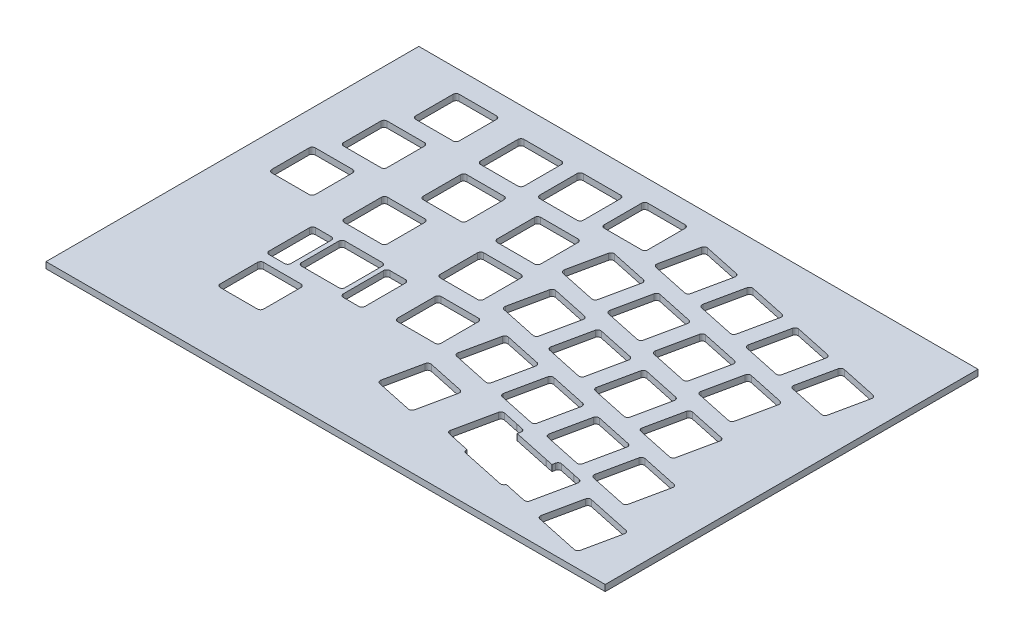
SolidWorks part; units mm, degrees
ref_plane "Front Plane" through (0, 0, 0) normal (0, 0, 1) x (1, 0, 0)
ref_plane "Top Plane" through (0, 0, 0) normal (0, 1, 0) x (1, 0, 0)
ref_plane "Right Plane" through (0, 0, 0) normal (1, 0, 0) x (0, 0, -1)
sketch "Sketch1" plane through (0, 0, 0) normal (0, 1, 0) x (1, 0, 0)
  line L1 (3, -3) -> (-177, -3) construction
  line L2 (3, -3) -> (3, 117) construction
  line L3 (3, 117) -> (-177, 117) construction
  line L4 (-177, -3) -> (-177, 117) construction
  line L5 (3, -3) -> (-177, 117) construction
  line L6 (3, 117) -> (-177, -3) construction
  line L15 (3, -3) -> (-177, -3)
  line L16 (3, -3) -> (3, 117)
  line L17 (3, 117) -> (-177, 117)
  line L18 (-177, -3) -> (-177, 117)
  line L19 (3, -3) -> (-177, 117) construction
  line L20 (3, 117) -> (-177, -3) construction
  point P5 (-87, 57)
  point P6 (-87, 57)
  line B0 (-26.8584, 37.7422) -> (-29.3534, 26.0044)
  line B1 (-28.5831, 24.8183) -> (-16.8454, 22.3234)
  line B2 (-13.1644, 34.8314) -> (-15.6593, 23.0936)
  line B3 (-25.6724, 38.5124) -> (-13.9346, 36.0175)
  line B4 (-32.2084, 58.3522) -> (-34.7034, 46.6144)
  line B5 (-33.9331, 45.4283) -> (-22.1954, 42.9334)
  line B6 (-18.5144, 55.4414) -> (-21.0093, 43.7036)
  line B7 (-31.0224, 59.1224) -> (-19.2846, 56.6275)
  line B8 (-32.9084, 77.9822) -> (-35.4034, 66.2444)
  line B9 (-34.6331, 65.0583) -> (-22.8954, 62.5634)
  line B10 (-19.2144, 75.0714) -> (-21.7093, 63.3336)
  line B11 (-31.7224, 78.7524) -> (-19.9846, 76.2575)
  line B12 (-19.6284, 94.6322) -> (-22.1234, 82.8944)
  line B13 (-21.3531, 81.7083) -> (-9.6154, 79.2134)
  line B14 (-5.9344, 91.7214) -> (-8.4293, 79.9836)
  line B15 (-18.4424, 95.4024) -> (-6.7046, 92.9075)
  line B16 (-45.4921, 41.7029) -> (-47.9871, 29.9651)
  line B17 (-47.2168, 28.7791) -> (-35.4791, 26.2841)
  line B18 (-31.7981, 38.7921) -> (-34.293, 27.0543)
  line B19 (-44.3061, 42.4731) -> (-32.5683, 39.9782)
  line B20 (-50.8421, 62.3129) -> (-53.3371, 50.5751)
  line B21 (-52.5668, 49.3891) -> (-40.8291, 46.8941)
  line B22 (-37.1481, 59.4021) -> (-39.643, 47.6643)
  line B23 (-49.6561, 63.0831) -> (-37.9183, 60.5882)
  line B24 (-51.5421, 81.9429) -> (-54.0371, 70.2051)
  line B25 (-53.2668, 69.0191) -> (-41.5291, 66.5241)
  line B26 (-37.8481, 79.0321) -> (-40.343, 67.2943)
  line B27 (-50.3561, 82.7131) -> (-38.6183, 80.2182)
  line B28 (-38.2621, 98.5929) -> (-40.7571, 86.8551)
  line B29 (-39.9868, 85.6691) -> (-28.2491, 83.1741)
  line B30 (-24.5681, 95.6821) -> (-27.063, 83.9443)
  line B31 (-37.0761, 99.3631) -> (-25.3383, 96.8682)
  line B32 (-64.1259, 45.6636) -> (-66.6208, 33.9258)
  line B33 (-65.8506, 32.7398) -> (-54.1128, 30.2448)
  line B34 (-50.4318, 42.7528) -> (-52.9267, 31.0151)
  line B35 (-62.9398, 46.4338) -> (-51.202, 43.9389)
  line B36 (-69.4759, 66.2736) -> (-71.9708, 54.5358)
  line B37 (-71.2006, 53.3498) -> (-59.4628, 50.8548)
  line B38 (-55.7818, 63.3628) -> (-58.2767, 51.6251)
  line B39 (-68.2898, 67.0438) -> (-56.552, 64.5489)
  line B40 (-70.1759, 85.9036) -> (-72.6708, 74.1658)
  line B41 (-71.9006, 72.9798) -> (-60.1628, 70.4848)
  line B42 (-56.4818, 82.9928) -> (-58.9767, 71.2551)
  line B43 (-68.9898, 86.6738) -> (-57.252, 84.1789)
  line B44 (-56.8959, 102.5536) -> (-59.3908, 90.8158)
  line B45 (-58.6206, 89.6298) -> (-46.8828, 87.1348)
  line B46 (-43.2018, 99.6428) -> (-45.6967, 87.9051)
  line B47 (-55.7098, 103.3238) -> (-43.972, 100.8289)
  line B48 (-88.1096, 70.2343) -> (-90.6045, 58.4965)
  line B49 (-89.8343, 57.3105) -> (-78.0965, 54.8155)
  line B50 (-74.4155, 67.3236) -> (-76.9104, 55.5858)
  line B51 (-86.9235, 71.0046) -> (-75.1857, 68.5096)
  line B52 (-82.7596, 49.6243) -> (-85.2545, 37.8865)
  line B53 (-84.4843, 36.7005) -> (-72.7465, 34.2055)
  line B54 (-69.0655, 46.7136) -> (-71.5604, 34.9758)
  line B55 (-81.5735, 50.3946) -> (-69.8357, 47.8996)
  line B56 (-87.5696, 29.6343) -> (-90.0645, 17.8965)
  line B57 (-89.2943, 16.7105) -> (-77.5565, 14.2155)
  line B58 (-73.8755, 26.7236) -> (-76.3704, 14.9858)
  line B59 (-86.3835, 30.4046) -> (-74.6457, 27.9096)
  line B60 (-88.8096, 89.8643) -> (-91.3045, 78.1265)
  line B61 (-90.5343, 76.9405) -> (-78.7965, 74.4455)
  line B62 (-75.1155, 86.9536) -> (-77.6104, 75.2158)
  line B63 (-87.6235, 90.6346) -> (-75.8857, 88.1396)
  line B64 (-75.5296, 106.5143) -> (-78.0245, 94.7765)
  line B65 (-77.2543, 93.5905) -> (-65.5165, 91.0955)
  line B66 (-61.8355, 103.6036) -> (-64.3304, 91.8658)
  line B67 (-74.3435, 107.2846) -> (-62.6057, 104.7896)
  line B68 (-110.01, 68.91) -> (-110.01, 56.91)
  line B69 (-109.01, 55.91) -> (-97.01, 55.91)
  line B70 (-96.01, 68.91) -> (-96.01, 56.91)
  line B71 (-109.01, 69.91) -> (-97.01, 69.91)
  line B72 (-134.52, 87.96) -> (-134.52, 75.96)
  line B73 (-133.52, 74.96) -> (-121.52, 74.96)
  line B74 (-120.52, 87.96) -> (-120.52, 75.96)
  line B75 (-133.52, 88.96) -> (-121.52, 88.96)
  line B76 (-140.97, 68.91) -> (-140.97, 56.91)
  line B77 (-139.97, 55.91) -> (-127.97, 55.91)
  line B78 (-126.97, 68.91) -> (-126.97, 56.91)
  line B79 (-139.97, 69.91) -> (-127.97, 69.91)
  line B80 (-110.71, 87.96) -> (-110.71, 75.96)
  line B81 (-109.71, 74.96) -> (-97.71, 74.96)
  line B82 (-96.71, 87.96) -> (-96.71, 75.96)
  line B83 (-109.71, 88.96) -> (-97.71, 88.96)
  line B84 (-97.43, 109.15) -> (-97.43, 97.15)
  line B85 (-96.43, 96.15) -> (-84.43, 96.15)
  line B86 (-83.43, 109.15) -> (-83.43, 97.15)
  line B87 (-96.43, 110.15) -> (-84.43, 110.15)
  line B88 (-116.07, 107.01) -> (-116.07, 95.01)
  line B89 (-115.07, 94.01) -> (-103.07, 94.01)
  line B90 (-102.07, 107.01) -> (-102.07, 95.01)
  line B91 (-115.07, 108.01) -> (-103.07, 108.01)
  line B92 (-135.12, 107.01) -> (-135.12, 95.01)
  line B93 (-134.12, 94.01) -> (-122.12, 94.01)
  line B94 (-121.12, 107.01) -> (-121.12, 95.01)
  line B95 (-134.12, 108.01) -> (-122.12, 108.01)
  line B96 (-104.66, 49.86) -> (-104.66, 37.86)
  line B97 (-103.66, 36.86) -> (-91.66, 36.86)
  line B98 (-90.66, 49.86) -> (-90.66, 37.86)
  line B99 (-103.66, 50.86) -> (-91.66, 50.86)
  line B100 (-142.75, 30.81) -> (-142.75, 18.81)
  line B101 (-141.75, 17.81) -> (-129.75, 17.81)
  line B102 (-128.75, 30.81) -> (-128.75, 18.81)
  line B103 (-141.75, 31.81) -> (-129.75, 31.81)
  line B104 (-158.14, 109.15) -> (-158.14, 97.15)
  line B105 (-157.14, 96.15) -> (-145.14, 96.15)
  line B106 (-144.14, 109.15) -> (-144.14, 97.15)
  line B107 (-157.14, 110.15) -> (-145.14, 110.15)
  line B108 (-162.3, 90.1) -> (-162.3, 78.1)
  line B109 (-161.3, 77.1) -> (-149.3, 77.1)
  line B110 (-148.3, 90.1) -> (-148.3, 78.1)
  line B111 (-161.3, 91.1) -> (-149.3, 91.1)
  line B112 (-135.61, 49.86) -> (-135.61, 37.86)
  line B113 (-134.61, 36.86) -> (-122.61, 36.86)
  line B114 (-121.61, 49.86) -> (-121.61, 37.86)
  line B115 (-134.61, 50.86) -> (-122.61, 50.86)
  line B116 (-166.37, 71.05) -> (-166.37, 59.05)
  line B117 (-165.37, 58.05) -> (-153.37, 58.05)
  line B118 (-152.37, 71.05) -> (-152.37, 59.05)
  line B119 (-165.37, 72.05) -> (-153.37, 72.05)
  line B120 (-113.172, 35.86) -> (-113.172, 48.86)
  line B121 (-114.172, 49.86) -> (-119.172, 49.86)
  line B122 (-120.172, 48.86) -> (-120.172, 35.86)
  line B123 (-119.172, 34.86) -> (-114.172, 34.86)
  line B124 (-137.048, 35.86) -> (-137.048, 48.86)
  line B125 (-138.048, 49.86) -> (-143.048, 49.86)
  line B126 (-144.048, 48.86) -> (-144.048, 35.86)
  line B127 (-143.048, 34.86) -> (-138.048, 34.86)
  line B128 (-53.7643, 10.6905) -> (-42.0265, 8.1955)
  line B129 (-40.8379, 8.9776) -> (-40.8404, 8.9658)
  line B130 (-38.5707, 8.4906) -> (-40.7417, 8.9521)
  line B131 (-38.4557, 8.4589) -> (-33.565, 7.4193)
  line B132 (-32.3789, 8.1896) -> (-29.6761, 20.9055)
  line B133 (-30.4463, 22.0915) -> (-32.6174, 22.553)
  line B134 (-32.7323, 22.5847) -> (-37.6231, 23.6243)
  line B135 (-38.8091, 22.8541) -> (-39.0195, 21.8641)
  line B136 (-41.3143, 22.3569) -> (-39.1157, 21.8896)
  line B137 (-41.4072, 22.3814) -> (-53.1449, 24.8763)
  line B138 (-53.2382, 24.8916) -> (-53.0303, 25.8696)
  line B139 (-53.8006, 27.0556) -> (-55.9716, 27.5171)
  line B140 (-56.0866, 27.5488) -> (-60.9773, 28.5884)
  line B141 (-62.1634, 27.8182) -> (-64.8662, 15.1022)
  line B142 (-61.9249, 13.4547) -> (-64.096, 13.9162)
  line B143 (-61.81, 13.423) -> (-56.9192, 12.3834)
  line B144 (-56.0557, 11.1823) -> (-53.8571, 10.7149)
  line B145 (-24.0476, 17.6691) -> (-26.5425, 5.9314)
  line B146 (-25.7723, 4.7453) -> (-11.7065, 1.7555)
  line B147 (-8.0255, 14.2636) -> (-10.5204, 2.5258)
  line B148 (-22.8615, 18.4394) -> (-8.7957, 15.4496)
  arc B149 (-29.3534, 26.0044) -> (-28.5831, 24.8183) centre (-28.3752, 25.7965) ccw
  arc B150 (-16.8454, 22.3234) -> (-15.6593, 23.0936) centre (-16.6374, 23.3015) ccw
  arc B151 (-13.1644, 34.8314) -> (-13.9346, 36.0175) centre (-14.1425, 35.0393) ccw
  arc B152 (-25.6724, 38.5124) -> (-26.8584, 37.7422) centre (-25.8803, 37.5343) ccw
  arc B153 (-34.7034, 46.6144) -> (-33.9331, 45.4283) centre (-33.7252, 46.4065) ccw
  arc B154 (-22.1954, 42.9334) -> (-21.0093, 43.7036) centre (-21.9874, 43.9115) ccw
  arc B155 (-18.5144, 55.4414) -> (-19.2846, 56.6275) centre (-19.4925, 55.6493) ccw
  arc B156 (-31.0224, 59.1224) -> (-32.2084, 58.3522) centre (-31.2303, 58.1443) ccw
  arc B157 (-35.4034, 66.2444) -> (-34.6331, 65.0583) centre (-34.4252, 66.0365) ccw
  arc B158 (-22.8954, 62.5634) -> (-21.7093, 63.3336) centre (-22.6874, 63.5415) ccw
  arc B159 (-19.2144, 75.0714) -> (-19.9846, 76.2575) centre (-20.1925, 75.2793) ccw
  arc B160 (-31.7224, 78.7524) -> (-32.9084, 77.9822) centre (-31.9303, 77.7743) ccw
  arc B161 (-22.1234, 82.8944) -> (-21.3531, 81.7083) centre (-21.1452, 82.6865) ccw
  arc B162 (-9.6154, 79.2134) -> (-8.4293, 79.9836) centre (-9.4074, 80.1915) ccw
  arc B163 (-5.9344, 91.7214) -> (-6.7046, 92.9075) centre (-6.9125, 91.9293) ccw
  arc B164 (-18.4424, 95.4024) -> (-19.6284, 94.6322) centre (-18.6503, 94.4243) ccw
  arc B165 (-47.9871, 29.9651) -> (-47.2168, 28.7791) centre (-47.0089, 29.7572) ccw
  arc B166 (-35.4791, 26.2841) -> (-34.293, 27.0543) centre (-35.2712, 27.2623) ccw
  arc B167 (-31.7981, 38.7921) -> (-32.5683, 39.9782) centre (-32.7762, 39) ccw
  arc B168 (-44.3061, 42.4731) -> (-45.4921, 41.7029) centre (-44.514, 41.495) ccw
  arc B169 (-53.3371, 50.5751) -> (-52.5668, 49.3891) centre (-52.3589, 50.3672) ccw
  arc B170 (-40.8291, 46.8941) -> (-39.643, 47.6643) centre (-40.6212, 47.8723) ccw
  arc B171 (-37.1481, 59.4021) -> (-37.9183, 60.5882) centre (-38.1262, 59.61) ccw
  arc B172 (-49.6561, 63.0831) -> (-50.8421, 62.3129) centre (-49.864, 62.105) ccw
  arc B173 (-54.0371, 70.2051) -> (-53.2668, 69.0191) centre (-53.0589, 69.9972) ccw
  arc B174 (-41.5291, 66.5241) -> (-40.343, 67.2943) centre (-41.3212, 67.5023) ccw
  arc B175 (-37.8481, 79.0321) -> (-38.6183, 80.2182) centre (-38.8262, 79.24) ccw
  arc B176 (-50.3561, 82.7131) -> (-51.5421, 81.9429) centre (-50.564, 81.735) ccw
  arc B177 (-40.7571, 86.8551) -> (-39.9868, 85.6691) centre (-39.7789, 86.6472) ccw
  arc B178 (-28.2491, 83.1741) -> (-27.063, 83.9443) centre (-28.0412, 84.1523) ccw
  arc B179 (-24.5681, 95.6821) -> (-25.3383, 96.8682) centre (-25.5462, 95.89) ccw
  arc B180 (-37.0761, 99.3631) -> (-38.2621, 98.5929) centre (-37.284, 98.385) ccw
  arc B181 (-66.6208, 33.9258) -> (-65.8506, 32.7398) centre (-65.6426, 33.7179) ccw
  arc B182 (-54.1128, 30.2448) -> (-52.9267, 31.0151) centre (-53.9049, 31.223) ccw
  arc B183 (-50.4318, 42.7528) -> (-51.202, 43.9389) centre (-51.4099, 42.9607) ccw
  arc B184 (-62.9398, 46.4338) -> (-64.1259, 45.6636) centre (-63.1477, 45.4557) ccw
  arc B185 (-71.9708, 54.5358) -> (-71.2006, 53.3498) centre (-70.9926, 54.3279) ccw
  arc B186 (-59.4628, 50.8548) -> (-58.2767, 51.6251) centre (-59.2549, 51.833) ccw
  arc B187 (-55.7818, 63.3628) -> (-56.552, 64.5489) centre (-56.7599, 63.5707) ccw
  arc B188 (-68.2898, 67.0438) -> (-69.4759, 66.2736) centre (-68.4977, 66.0657) ccw
  arc B189 (-72.6708, 74.1658) -> (-71.9006, 72.9798) centre (-71.6926, 73.9579) ccw
  arc B190 (-60.1628, 70.4848) -> (-58.9767, 71.2551) centre (-59.9549, 71.463) ccw
  arc B191 (-56.4818, 82.9928) -> (-57.252, 84.1789) centre (-57.4599, 83.2007) ccw
  arc B192 (-68.9898, 86.6738) -> (-70.1759, 85.9036) centre (-69.1977, 85.6957) ccw
  arc B193 (-59.3908, 90.8158) -> (-58.6206, 89.6298) centre (-58.4126, 90.6079) ccw
  arc B194 (-46.8828, 87.1348) -> (-45.6967, 87.9051) centre (-46.6749, 88.113) ccw
  arc B195 (-43.2018, 99.6428) -> (-43.972, 100.8289) centre (-44.1799, 99.8507) ccw
  arc B196 (-55.7098, 103.3238) -> (-56.8959, 102.5536) centre (-55.9177, 102.3457) ccw
  arc B197 (-90.6045, 58.4965) -> (-89.8343, 57.3105) centre (-89.6264, 58.2886) ccw
  arc B198 (-78.0965, 54.8155) -> (-76.9104, 55.5858) centre (-77.8886, 55.7937) ccw
  arc B199 (-74.4155, 67.3236) -> (-75.1857, 68.5096) centre (-75.3936, 67.5315) ccw
  arc B200 (-86.9235, 71.0046) -> (-88.1096, 70.2343) centre (-87.1314, 70.0264) ccw
  arc B201 (-85.2545, 37.8865) -> (-84.4843, 36.7005) centre (-84.2764, 37.6786) ccw
  arc B202 (-72.7465, 34.2055) -> (-71.5604, 34.9758) centre (-72.5386, 35.1837) ccw
  arc B203 (-69.0655, 46.7136) -> (-69.8357, 47.8996) centre (-70.0436, 46.9215) ccw
  arc B204 (-81.5735, 50.3946) -> (-82.7596, 49.6243) centre (-81.7814, 49.4164) ccw
  arc B205 (-90.0645, 17.8965) -> (-89.2943, 16.7105) centre (-89.0864, 17.6886) ccw
  arc B206 (-77.5565, 14.2155) -> (-76.3704, 14.9858) centre (-77.3486, 15.1937) ccw
  arc B207 (-73.8755, 26.7236) -> (-74.6457, 27.9096) centre (-74.8536, 26.9315) ccw
  arc B208 (-86.3835, 30.4046) -> (-87.5696, 29.6343) centre (-86.5914, 29.4264) ccw
  arc B209 (-91.3045, 78.1265) -> (-90.5343, 76.9405) centre (-90.3264, 77.9186) ccw
  arc B210 (-78.7965, 74.4455) -> (-77.6104, 75.2158) centre (-78.5886, 75.4237) ccw
  arc B211 (-75.1155, 86.9536) -> (-75.8857, 88.1396) centre (-76.0936, 87.1615) ccw
  arc B212 (-87.6235, 90.6346) -> (-88.8096, 89.8643) centre (-87.8314, 89.6564) ccw
  arc B213 (-78.0245, 94.7765) -> (-77.2543, 93.5905) centre (-77.0464, 94.5686) ccw
  arc B214 (-65.5165, 91.0955) -> (-64.3304, 91.8658) centre (-65.3086, 92.0737) ccw
  arc B215 (-61.8355, 103.6036) -> (-62.6057, 104.7896) centre (-62.8136, 103.8115) ccw
  arc B216 (-74.3435, 107.2846) -> (-75.5296, 106.5143) centre (-74.5514, 106.3064) ccw
  arc B217 (-110.01, 56.91) -> (-109.01, 55.91) centre (-109.01, 56.91) ccw
  arc B218 (-97.01, 55.91) -> (-96.01, 56.91) centre (-97.01, 56.91) ccw
  arc B219 (-96.01, 68.91) -> (-97.01, 69.91) centre (-97.01, 68.91) ccw
  arc B220 (-109.01, 69.91) -> (-110.01, 68.91) centre (-109.01, 68.91) ccw
  arc B221 (-134.52, 75.96) -> (-133.52, 74.96) centre (-133.52, 75.96) ccw
  arc B222 (-121.52, 74.96) -> (-120.52, 75.96) centre (-121.52, 75.96) ccw
  arc B223 (-120.52, 87.96) -> (-121.52, 88.96) centre (-121.52, 87.96) ccw
  arc B224 (-133.52, 88.96) -> (-134.52, 87.96) centre (-133.52, 87.96) ccw
  arc B225 (-140.97, 56.91) -> (-139.97, 55.91) centre (-139.97, 56.91) ccw
  arc B226 (-127.97, 55.91) -> (-126.97, 56.91) centre (-127.97, 56.91) ccw
  arc B227 (-126.97, 68.91) -> (-127.97, 69.91) centre (-127.97, 68.91) ccw
  arc B228 (-139.97, 69.91) -> (-140.97, 68.91) centre (-139.97, 68.91) ccw
  arc B229 (-110.71, 75.96) -> (-109.71, 74.96) centre (-109.71, 75.96) ccw
  arc B230 (-97.71, 74.96) -> (-96.71, 75.96) centre (-97.71, 75.96) ccw
  arc B231 (-96.71, 87.96) -> (-97.71, 88.96) centre (-97.71, 87.96) ccw
  arc B232 (-109.71, 88.96) -> (-110.71, 87.96) centre (-109.71, 87.96) ccw
  arc B233 (-97.43, 97.15) -> (-96.43, 96.15) centre (-96.43, 97.15) ccw
  arc B234 (-84.43, 96.15) -> (-83.43, 97.15) centre (-84.43, 97.15) ccw
  arc B235 (-83.43, 109.15) -> (-84.43, 110.15) centre (-84.43, 109.15) ccw
  arc B236 (-96.43, 110.15) -> (-97.43, 109.15) centre (-96.43, 109.15) ccw
  arc B237 (-116.07, 95.01) -> (-115.07, 94.01) centre (-115.07, 95.01) ccw
  arc B238 (-103.07, 94.01) -> (-102.07, 95.01) centre (-103.07, 95.01) ccw
  arc B239 (-102.07, 107.01) -> (-103.07, 108.01) centre (-103.07, 107.01) ccw
  arc B240 (-115.07, 108.01) -> (-116.07, 107.01) centre (-115.07, 107.01) ccw
  arc B241 (-135.12, 95.01) -> (-134.12, 94.01) centre (-134.12, 95.01) ccw
  arc B242 (-122.12, 94.01) -> (-121.12, 95.01) centre (-122.12, 95.01) ccw
  arc B243 (-121.12, 107.01) -> (-122.12, 108.01) centre (-122.12, 107.01) ccw
  arc B244 (-134.12, 108.01) -> (-135.12, 107.01) centre (-134.12, 107.01) ccw
  arc B245 (-104.66, 37.86) -> (-103.66, 36.86) centre (-103.66, 37.86) ccw
  arc B246 (-91.66, 36.86) -> (-90.66, 37.86) centre (-91.66, 37.86) ccw
  arc B247 (-90.66, 49.86) -> (-91.66, 50.86) centre (-91.66, 49.86) ccw
  arc B248 (-103.66, 50.86) -> (-104.66, 49.86) centre (-103.66, 49.86) ccw
  arc B249 (-142.75, 18.81) -> (-141.75, 17.81) centre (-141.75, 18.81) ccw
  arc B250 (-129.75, 17.81) -> (-128.75, 18.81) centre (-129.75, 18.81) ccw
  arc B251 (-128.75, 30.81) -> (-129.75, 31.81) centre (-129.75, 30.81) ccw
  arc B252 (-141.75, 31.81) -> (-142.75, 30.81) centre (-141.75, 30.81) ccw
  arc B253 (-158.14, 97.15) -> (-157.14, 96.15) centre (-157.14, 97.15) ccw
  arc B254 (-145.14, 96.15) -> (-144.14, 97.15) centre (-145.14, 97.15) ccw
  arc B255 (-144.14, 109.15) -> (-145.14, 110.15) centre (-145.14, 109.15) ccw
  arc B256 (-157.14, 110.15) -> (-158.14, 109.15) centre (-157.14, 109.15) ccw
  arc B257 (-162.3, 78.1) -> (-161.3, 77.1) centre (-161.3, 78.1) ccw
  arc B258 (-149.3, 77.1) -> (-148.3, 78.1) centre (-149.3, 78.1) ccw
  arc B259 (-148.3, 90.1) -> (-149.3, 91.1) centre (-149.3, 90.1) ccw
  arc B260 (-161.3, 91.1) -> (-162.3, 90.1) centre (-161.3, 90.1) ccw
  arc B261 (-135.61, 37.86) -> (-134.61, 36.86) centre (-134.61, 37.86) ccw
  arc B262 (-122.61, 36.86) -> (-121.61, 37.86) centre (-122.61, 37.86) ccw
  arc B263 (-121.61, 49.86) -> (-122.61, 50.86) centre (-122.61, 49.86) ccw
  arc B264 (-134.61, 50.86) -> (-135.61, 49.86) centre (-134.61, 49.86) ccw
  arc B265 (-166.37, 59.05) -> (-165.37, 58.05) centre (-165.37, 59.05) ccw
  arc B266 (-153.37, 58.05) -> (-152.37, 59.05) centre (-153.37, 59.05) ccw
  arc B267 (-152.37, 71.05) -> (-153.37, 72.05) centre (-153.37, 71.05) ccw
  arc B268 (-165.37, 72.05) -> (-166.37, 71.05) centre (-165.37, 71.05) ccw
  arc B269 (-113.172, 48.86) -> (-114.172, 49.86) centre (-114.172, 48.86) ccw
  arc B270 (-119.172, 49.86) -> (-120.172, 48.86) centre (-119.172, 48.86) ccw
  arc B271 (-120.172, 35.86) -> (-119.172, 34.86) centre (-119.172, 35.86) ccw
  arc B272 (-114.172, 34.86) -> (-113.172, 35.86) centre (-114.172, 35.86) ccw
  arc B273 (-137.048, 48.86) -> (-138.048, 49.86) centre (-138.048, 48.86) ccw
  arc B274 (-143.048, 49.86) -> (-144.048, 48.86) centre (-143.048, 48.86) ccw
  arc B275 (-144.048, 35.86) -> (-143.048, 34.86) centre (-143.048, 35.86) ccw
  arc B276 (-138.048, 34.86) -> (-137.048, 35.86) centre (-138.048, 35.86) ccw
  arc B277 (-53.8571, 10.7149) -> (-53.7643, 10.6905) centre (-53.5564, 11.6686) ccw
  arc B278 (-42.0265, 8.1955) -> (-40.8404, 8.9658) centre (-41.8186, 9.1737) ccw
  arc B279 (-40.8379, 8.9776) -> (-40.7417, 8.9521) centre (-40.5338, 9.9302) ccw
  arc B280 (-38.5707, 8.4906) -> (-38.4557, 8.4589) centre (-38.2478, 9.437) ccw
  arc B281 (-33.565, 7.4193) -> (-32.3789, 8.1896) centre (-33.3571, 8.3975) ccw
  arc B282 (-29.6761, 20.9055) -> (-30.4463, 22.0915) centre (-30.6542, 21.1134) ccw
  arc B283 (-32.6174, 22.553) -> (-32.7323, 22.5847) centre (-32.9402, 21.6066) ccw
  arc B284 (-37.6231, 23.6243) -> (-38.8091, 22.8541) centre (-37.831, 22.6461) ccw
  arc B285 (-39.0195, 21.8641) -> (-39.1157, 21.8896) centre (-39.3236, 20.9115) ccw
  arc B286 (-41.3143, 22.3569) -> (-41.4072, 22.3814) centre (-41.6151, 21.4032) ccw
  arc B287 (-53.1449, 24.8763) -> (-53.2382, 24.8916) centre (-53.3529, 23.8982) ccw
  arc B288 (-53.0303, 25.8696) -> (-53.8006, 27.0556) centre (-54.0085, 26.0775) ccw
  arc B289 (-55.9716, 27.5171) -> (-56.0866, 27.5488) centre (-56.2945, 26.5707) ccw
  arc B290 (-60.9773, 28.5884) -> (-62.1634, 27.8182) centre (-61.1852, 27.6102) ccw
  arc B291 (-64.8662, 15.1022) -> (-64.096, 13.9162) centre (-63.8881, 14.8943) ccw
  arc B292 (-61.9249, 13.4547) -> (-61.81, 13.423) centre (-61.6021, 14.4011) ccw
  arc B293 (-56.9192, 12.3834) -> (-56.826, 12.3682) centre (-56.7113, 13.3616) ccw
  arc B294 (-56.826, 12.3682) -> (-56.0557, 11.1823) centre (-55.8478, 12.1604) ccw
  arc B295 (-26.5425, 5.9314) -> (-25.7723, 4.7453) centre (-25.5643, 5.7235) ccw
  arc B296 (-11.7065, 1.7555) -> (-10.5204, 2.5258) centre (-11.4986, 2.7337) ccw
  arc B297 (-8.0255, 14.2636) -> (-8.7957, 15.4496) centre (-9.0036, 14.4715) ccw
  arc B298 (-22.8615, 18.4394) -> (-24.0476, 17.6691) centre (-23.0694, 17.4612) ccw
  dimension "D1" = 120
  dimension "D2" = 180
  dimension "D3" = 3
  dimension "D4" = 3
sketch_block_instance "alice-split-left-side-1"
sketch_block "alice-split-left-side"
extrude "Boss-Extrude1" add sketch "Sketch1" along normal mid plane 2
